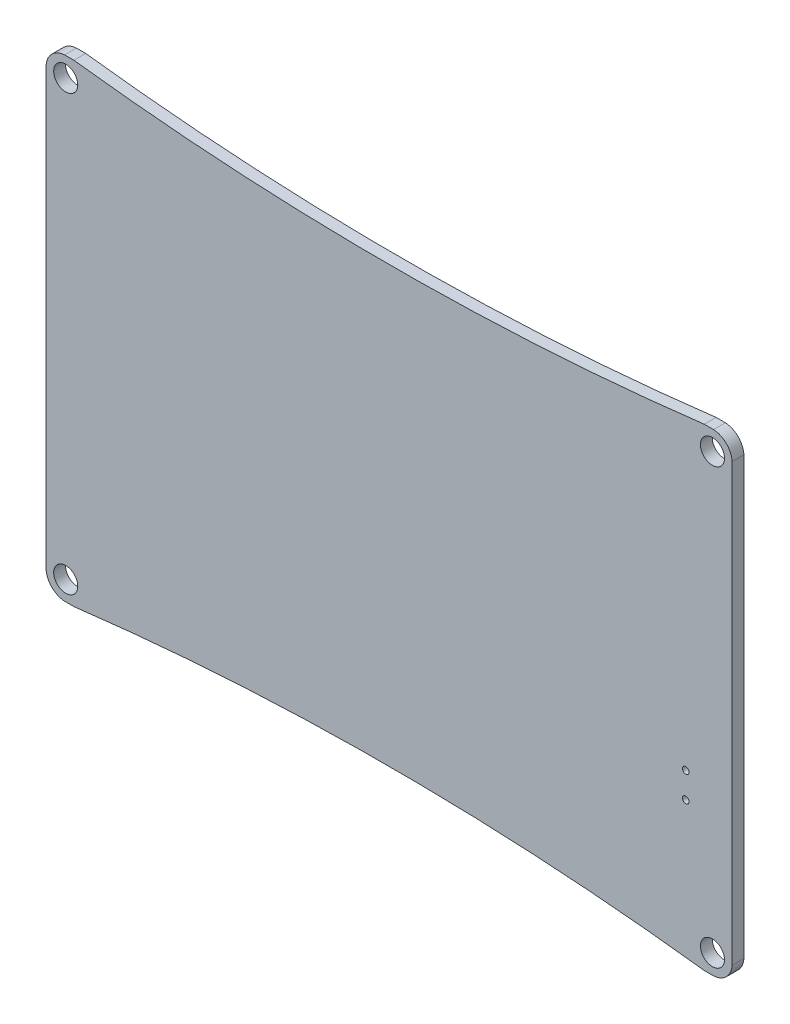
SolidWorks part; units mm, degrees
ref_plane "Front Plane" through (0, 0, 0) normal (0, 0, 1) x (1, 0, 0)
ref_plane "Top Plane" through (0, 0, 0) normal (0, 1, 0) x (1, 0, 0)
ref_plane "Right Plane" through (0, 0, 0) normal (1, 0, 0) x (0, 0, -1)
sketch "Sketch1" plane through (0, 0, 0) normal (0, 0, 1) x (1, 0, 0)
  line L0 (2.54, 62.89) -> (2.54, 3.15)
  line L1 (5.08, 0.61) -> (6.35, 0.61)
  line L2 (92.71, 0.61) -> (93.98, 0.61)
  line L3 (96.52, 3.15) -> (96.52, 62.89)
  line L4 (93.98, 65.43) -> (92.71, 65.43)
  line L5 (6.35, 65.43) -> (5.08, 65.43)
  arc A0 (2.54, 3.15) -> (5.08, 0.61) centre (5.2205, 3.2905) ccw
  arc A1 (6.35, 0.61) -> (92.71, 0.61) centre (49.53, -351.0629) cw
  arc A2 (93.98, 0.61) -> (96.52, 3.15) centre (93.8395, 3.2905) ccw
  arc A3 (96.52, 62.89) -> (93.98, 65.43) centre (93.8395, 62.7495) ccw
  arc A4 (92.71, 65.43) -> (6.35, 65.43) centre (49.53, 417.1029) cw
  arc A5 (5.08, 65.43) -> (2.54, 62.89) centre (5.2205, 62.7495) ccw
extrude "Board_Outline" add sketch "Sketch1" along normal blind 1.62 separate body
sketch "Sketch2" plane through (0, 0, 0) normal (0, 0, 1) x (1, 0, 0)
  circle A0 centre (90.17, 23.09) radius 0.45
  circle A1 centre (90.17, 19.59) radius 0.45
extrude "NPTH" cut sketch "Sketch2" along normal through all
sketch "Sketch3" plane through (0, 0, 0) normal (0, 0, 1) x (1, 0, 0)
  circle A0 centre (93.83, 3.28) radius 1.65
  circle A1 centre (5.23, 3.28) radius 1.65
  circle A2 centre (5.23, 62.76) radius 1.65
  circle A3 centre (93.83, 62.76) radius 1.65
extrude "PTH" cut sketch "Sketch3" along normal through all
